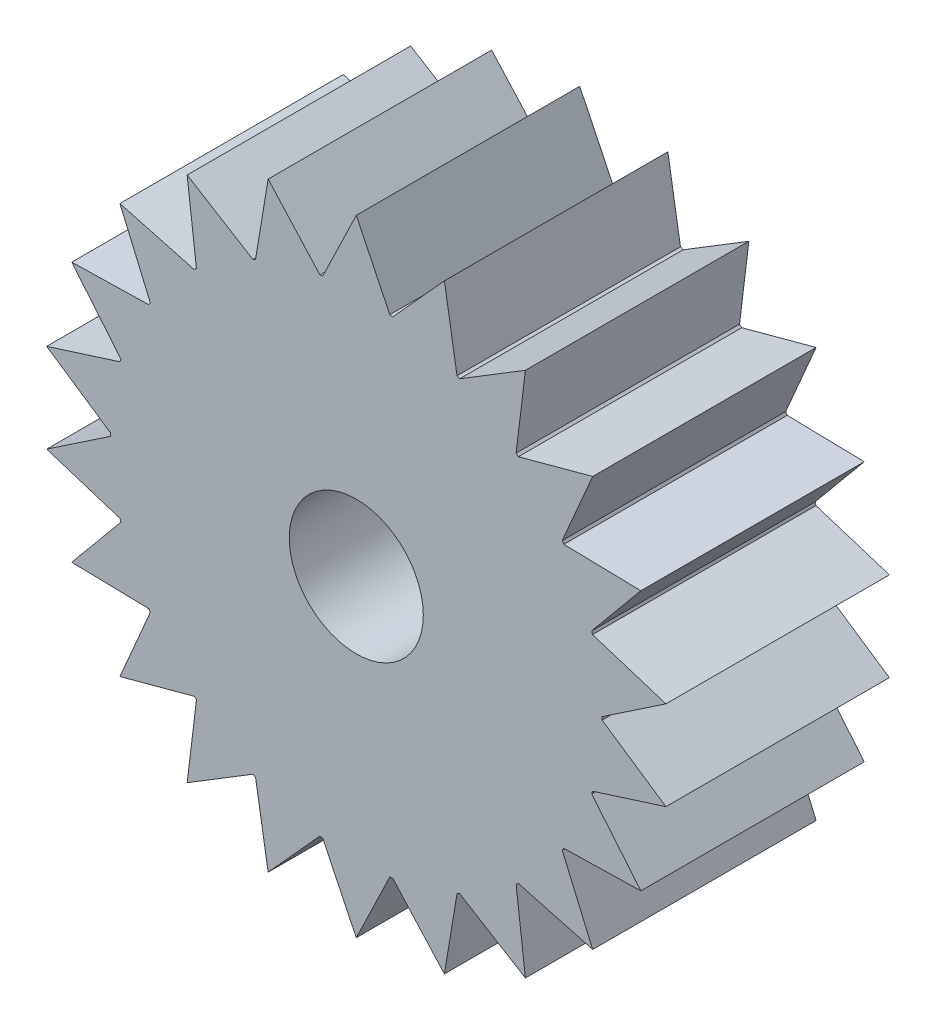
SolidWorks part; units mm, degrees
ref_plane "Plan de face" through (0, 0, 0) normal (0, 0, 1) x (1, 0, 0)
ref_plane "Plan de dessus" through (0, 0, 0) normal (0, 1, 0) x (1, 0, 0)
ref_plane "Plan de droite" through (0, 0, 0) normal (1, 0, 0) x (0, 0, -1)
sketch "Esquisse2" plane through (0, 0, 0) normal (1, 0, 0) x (0, 0, -1)
  line L0 (0, 3) -> (0, 11)
  line L1 (0, 11) -> (10, 11)
  line L2 (10, 11) -> (10, 3)
  line L3 (10, 3) -> (0, 3)
  line L4 (0, 0) -> (0.4045, 0) construction
  dimension "D1" = 3
  dimension "D2" = 8
  dimension "D3" = 10
revolve "Révolution1" add sketch "Esquisse2" angle 360 about L4
sketch "Esquisse3" plane through (0, 0, 0) normal (0, 0, 1) x (1, 0, 0)
  line L0 (0, 11) -> (0, 14) construction
  line L1 (0, 14) -> (-1.5, 10.8972)
  line L2 (0, 14) -> (1.5, 10.8972)
  line L3 (3.9443, 13.4329) -> (4.5093, 10.0332)
  line L4 (3.9443, 13.4329) -> (1.6309, 10.8784)
  line L5 (7.569, 11.7775) -> (7.1534, 8.3564)
  line L6 (7.569, 11.7775) -> (4.6296, 9.9783)
  line L7 (10.5805, 9.1681) -> (9.2179, 6.0026)
  line L8 (10.5805, 9.1681) -> (7.2533, 8.2698)
  line L9 (12.7348, 5.8158) -> (10.5356, 3.1624)
  line L10 (12.7348, 5.8158) -> (9.2894, 5.8913)
  line L11 (13.8575, 1.9924) -> (10.9998, 0.0661)
  line L12 (13.8575, 1.9924) -> (10.5729, 3.0356)
  line L13 (13.8575, -1.9924) -> (10.5729, -3.0356)
  line L14 (13.8575, -1.9924) -> (10.9998, -0.0661)
  line L15 (12.7348, -5.8158) -> (9.2894, -5.8913)
  line L16 (12.7348, -5.8158) -> (10.5356, -3.1624)
  line L17 (10.5805, -9.1681) -> (7.2533, -8.2698)
  line L18 (10.5805, -9.1681) -> (9.2179, -6.0026)
  line L19 (7.569, -11.7775) -> (4.6296, -9.9783)
  line L20 (7.569, -11.7775) -> (7.1534, -8.3564)
  line L21 (3.9443, -13.4329) -> (1.6309, -10.8784)
  line L22 (3.9443, -13.4329) -> (4.5093, -10.0332)
  line L23 (0, -14) -> (-1.5, -10.8972)
  line L24 (0, -14) -> (1.5, -10.8972)
  line L25 (-3.9443, -13.4329) -> (-4.5093, -10.0332)
  line L26 (-3.9443, -13.4329) -> (-1.6309, -10.8784)
  line L27 (-7.569, -11.7775) -> (-7.1534, -8.3564)
  line L28 (-7.569, -11.7775) -> (-4.6296, -9.9783)
  line L29 (-10.5805, -9.1681) -> (-9.2179, -6.0026)
  line L30 (-10.5805, -9.1681) -> (-7.2533, -8.2698)
  line L31 (-12.7348, -5.8158) -> (-10.5356, -3.1624)
  line L32 (-12.7348, -5.8158) -> (-9.2894, -5.8913)
  line L33 (-13.8575, -1.9924) -> (-10.9998, -0.0661)
  line L34 (-13.8575, -1.9924) -> (-10.5729, -3.0356)
  line L35 (-13.8575, 1.9924) -> (-10.5729, 3.0356)
  line L36 (-13.8575, 1.9924) -> (-10.9998, 0.0661)
  line L37 (-12.7348, 5.8158) -> (-9.2894, 5.8913)
  line L38 (-12.7348, 5.8158) -> (-10.5356, 3.1624)
  line L39 (-10.5805, 9.1681) -> (-7.2533, 8.2698)
  line L40 (-10.5805, 9.1681) -> (-9.2179, 6.0026)
  line L41 (-7.569, 11.7775) -> (-4.6296, 9.9783)
  line L42 (-7.569, 11.7775) -> (-7.1534, 8.3564)
  line L43 (-3.9443, 13.4329) -> (-1.6309, 10.8784)
  line L44 (-3.9443, 13.4329) -> (-4.5093, 10.0332)
  circle A0 centre (0, 0) radius 11 construction
  arc A1 (0, 11) -> (-1.5, 10.8972) centre (0, 0) ccw
  arc A2 (0, 11) -> (1.5, 10.8972) centre (0, 0) cw
  arc A3 (3.0991, 10.5544) -> (1.6309, 10.8784) centre (0, 0) ccw
  arc A4 (3.0991, 10.5544) -> (4.5093, 10.0332) centre (0, 0) cw
  arc A5 (5.947, 9.2538) -> (4.6296, 9.9783) centre (0, 0) ccw
  arc A6 (5.947, 9.2538) -> (7.1534, 8.3564) centre (0, 0) cw
  arc A7 (8.3132, 7.2035) -> (7.2533, 8.2698) centre (0, 0) ccw
  arc A8 (8.3132, 7.2035) -> (9.2179, 6.0026) centre (0, 0) cw
  arc A9 (10.006, 4.5696) -> (9.2894, 5.8913) centre (0, 0) ccw
  arc A10 (10.006, 4.5696) -> (10.5356, 3.1624) centre (0, 0) cw
  arc A11 (10.888, 1.5655) -> (10.5729, 3.0356) centre (0, 0) ccw
  arc A12 (10.888, 1.5655) -> (10.9998, 0.0661) centre (0, 0) cw
  arc A13 (10.888, -1.5655) -> (10.9998, -0.0661) centre (0, 0) ccw
  arc A14 (10.888, -1.5655) -> (10.5729, -3.0356) centre (0, 0) cw
  arc A15 (10.006, -4.5696) -> (10.5356, -3.1624) centre (0, 0) ccw
  arc A16 (10.006, -4.5696) -> (9.2894, -5.8913) centre (0, 0) cw
  arc A17 (8.3132, -7.2035) -> (9.2179, -6.0026) centre (0, 0) ccw
  arc A18 (8.3132, -7.2035) -> (7.2533, -8.2698) centre (0, 0) cw
  arc A19 (5.947, -9.2538) -> (7.1534, -8.3564) centre (0, 0) ccw
  arc A20 (5.947, -9.2538) -> (4.6296, -9.9783) centre (0, 0) cw
  arc A21 (3.0991, -10.5544) -> (4.5093, -10.0332) centre (0, 0) ccw
  arc A22 (3.0991, -10.5544) -> (1.6309, -10.8784) centre (0, 0) cw
  arc A23 (0, -11) -> (1.5, -10.8972) centre (0, 0) ccw
  arc A24 (0, -11) -> (-1.5, -10.8972) centre (0, 0) cw
  arc A25 (-3.0991, -10.5544) -> (-1.6309, -10.8784) centre (0, 0) ccw
  arc A26 (-3.0991, -10.5544) -> (-4.5093, -10.0332) centre (0, 0) cw
  arc A27 (-5.947, -9.2538) -> (-4.6296, -9.9783) centre (0, 0) ccw
  arc A28 (-5.947, -9.2538) -> (-7.1534, -8.3564) centre (0, 0) cw
  arc A29 (-8.3132, -7.2035) -> (-7.2533, -8.2698) centre (0, 0) ccw
  arc A30 (-8.3132, -7.2035) -> (-9.2179, -6.0026) centre (0, 0) cw
  arc A31 (-10.006, -4.5696) -> (-9.2894, -5.8913) centre (0, 0) ccw
  arc A32 (-10.006, -4.5696) -> (-10.5356, -3.1624) centre (0, 0) cw
  arc A33 (-10.888, -1.5655) -> (-10.5729, -3.0356) centre (0, 0) ccw
  arc A34 (-10.888, -1.5655) -> (-10.9998, -0.0661) centre (0, 0) cw
  arc A35 (-10.888, 1.5655) -> (-10.9998, 0.0661) centre (0, 0) ccw
  arc A36 (-10.888, 1.5655) -> (-10.5729, 3.0356) centre (0, 0) cw
  arc A37 (-10.006, 4.5696) -> (-10.5356, 3.1624) centre (0, 0) ccw
  arc A38 (-10.006, 4.5696) -> (-9.2894, 5.8913) centre (0, 0) cw
  arc A39 (-8.3132, 7.2035) -> (-9.2179, 6.0026) centre (0, 0) ccw
  arc A40 (-8.3132, 7.2035) -> (-7.2533, 8.2698) centre (0, 0) cw
  arc A41 (-5.947, 9.2538) -> (-7.1534, 8.3564) centre (0, 0) ccw
  arc A42 (-5.947, 9.2538) -> (-4.6296, 9.9783) centre (0, 0) cw
  arc A43 (-3.0991, 10.5544) -> (-4.5093, 10.0332) centre (0, 0) ccw
  arc A44 (-3.0991, 10.5544) -> (-1.6309, 10.8784) centre (0, 0) cw
  point P97 (0, 0)
  dimension "D1" = 1.5
  dimension "D2" = 3
  dimension "D3" = 22
extrude "Boss.-Extru.1" add sketch "Esquisse3" against normal blind 10
